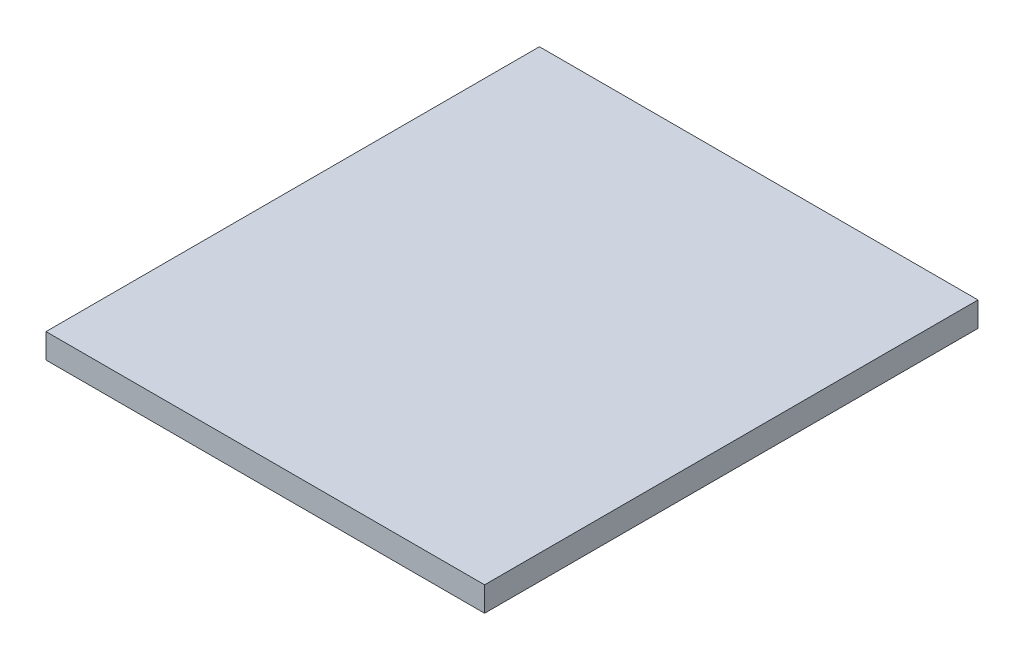
SolidWorks part; units mm, degrees
material "Poplar plywood painted"
ref_plane "Front Plane" through (0, 0, 0) normal (0, 0, 1) x (1, 0, 0)
ref_plane "Top Plane" through (0, 0, 0) normal (0, 1, 0) x (1, 0, 0)
ref_plane "Right Plane" through (0, 0, 0) normal (1, 0, 0) x (0, 0, -1)
sketch "Sketch1" plane through (0, 0, 0) normal (0, 1, 0) x (1, 0, 0)
  line L0 (-80, 90) -> (80, -90) construction
  line L1 (-80, 90) -> (80, 90)
  line L2 (-80, 90) -> (-80, -90)
  line L3 (-80, -90) -> (80, -90)
  line L4 (80, 90) -> (80, -90)
  dimension "D1" = 160
  dimension "D2" = 180
extrude "Boss-Extrude1" add sketch "Sketch1" along normal mid plane 9
